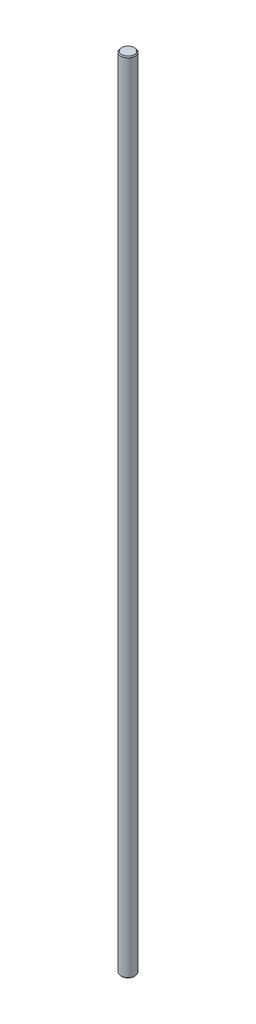
SolidWorks part; units mm, degrees
material "Acero inoxidable al cromo"
ref_plane "Alzado" through (0, 0, 0) normal (0, 0, 1) x (1, 0, 0)
ref_plane "Planta" through (0, 0, 0) normal (0, 1, 0) x (1, 0, 0)
ref_plane "Vista lateral" through (0, 0, 0) normal (1, 0, 0) x (0, 0, -1)
sketch "Croquis1" plane through (0, 0, 0) normal (0, 1, 0) x (1, 0, 0)
  circle A0 centre (0, 0) radius 4
  circle A1 centre (0, 0) radius 3 construction
  dimension "D1" = 8
  dimension "D2" = 6
extrude "Saliente-Extruir1" add sketch "Croquis1" along normal blind 450
chamfer "Chaflán1" distance 0.5 angle 45 2 edges at (0, 0, 4) (0, 450, 4)
